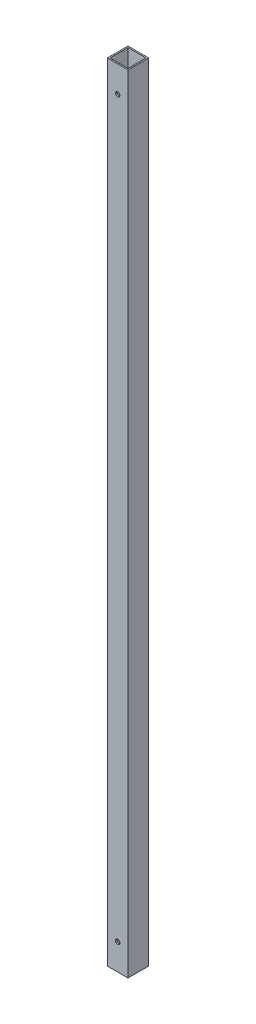
SolidWorks part; units mm, degrees
ref_plane "Front Plane" through (0, 0, 0) normal (0, 0, 1) x (1, 0, 0)
ref_plane "Top Plane" through (0, 0, 0) normal (0, 1, 0) x (1, 0, 0)
ref_plane "Right Plane" through (0, 0, 0) normal (1, 0, 0) x (0, 0, -1)
sketch "Sketch1" plane through (0, 0, 0) normal (0, 1, 0) x (1, 0, 0)
  line L0 (-6.9, -6.9) -> (-6.9, 6.9)
  line L1 (-7.9, -7.9) -> (7.9, -7.9)
  line L2 (-7.9, -7.9) -> (-7.9, 7.9)
  line L3 (-7.9, 7.9) -> (7.9, 7.9)
  line L4 (7.9, -7.9) -> (7.9, 7.9)
  line L5 (-7.9, -7.9) -> (7.9, 7.9) construction
  line L6 (-7.9, 7.9) -> (7.9, -7.9) construction
  line L7 (-6.9, 6.9) -> (6.9, 6.9)
  line L8 (6.9, -6.9) -> (6.9, 6.9)
  line L9 (-6.9, -6.9) -> (6.9, -6.9)
  point P0 (0, 0)
  dimension "D1" = 1
extrude "Boss-Extrude1" add sketch "Sketch1" along normal blind 600
sketch "Sketch3" plane through (0, 0, 7.9) normal (0, 0, 1) x (1, 0, 0)
  circle A0 centre (0, 580) radius 1.7
  circle A1 centre (0, 20) radius 1.7
  dimension "D1" = 3.4
  dimension "D2" = 3.4
extrude "Cut-Extrude2" cut sketch "Sketch3" against normal through all
